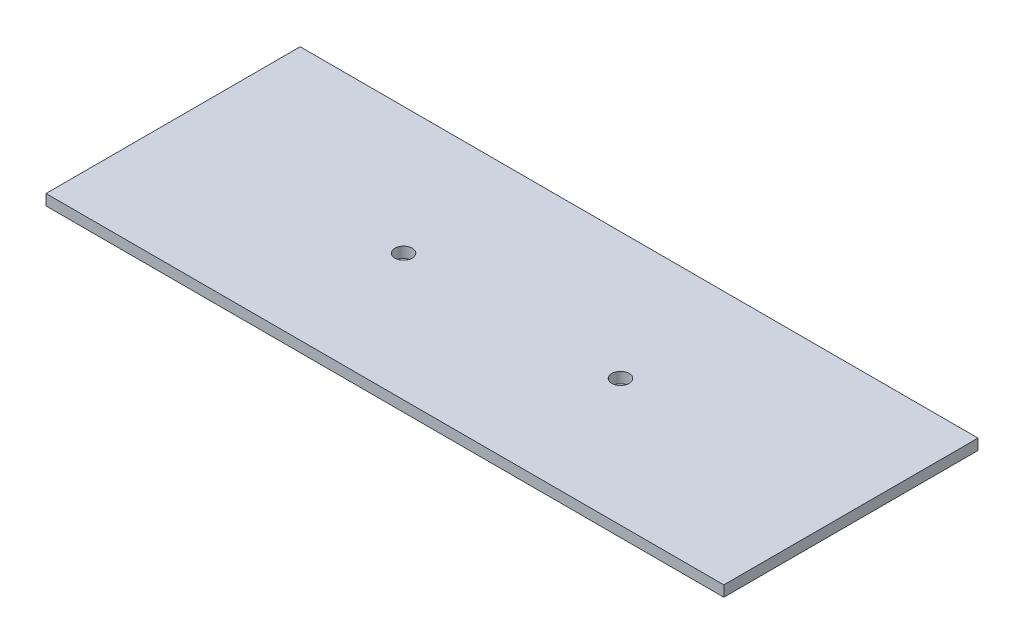
SolidWorks part; units mm, degrees
material "Acrylic (Medium-high impact)"
ref_plane "Front Plane" through (0, 0, 0) normal (0, 0, 1) x (1, 0, 0)
ref_plane "Top Plane" through (0, 0, 0) normal (0, 1, 0) x (1, 0, 0)
ref_plane "Right Plane" through (0, 0, 0) normal (1, 0, 0) x (0, 0, -1)
sketch "Sketch1" plane through (0, 0, 0) normal (0, 1, 0) x (1, 0, 0)
  line L1 (-100, -37.5) -> (100, -37.5)
  line L2 (-100, -37.5) -> (-100, 37.5)
  line L3 (-100, 37.5) -> (100, 37.5)
  line L4 (100, -37.5) -> (100, 37.5)
  line L5 (-100, -37.5) -> (100, 37.5) construction
  line L6 (-100, 37.5) -> (100, -37.5) construction
  point P0 (0, 0)
  dimension "D1" = 75
  dimension "D2" = 200
extrude "Boss-Extrude1" add sketch "Sketch1" along normal blind 3.175
sketch "Sketch2" plane through (0, 3.175, 0) normal (0, 1, 0) x (1, 0, 0)
  line L0 (-114.6651, 0) -> (112.9423, 0) construction
  line L1 (0, -56.1855) -> (0, 62.13) construction
  circle A0 centre (32, 0) radius 2.5527
  circle A1 centre (-32, 0) radius 2.5527
  dimension "D1" = 5.1054
  dimension "D2" = 32
extrude "Cut-Extrude1" cut sketch "Sketch2" against normal through all
